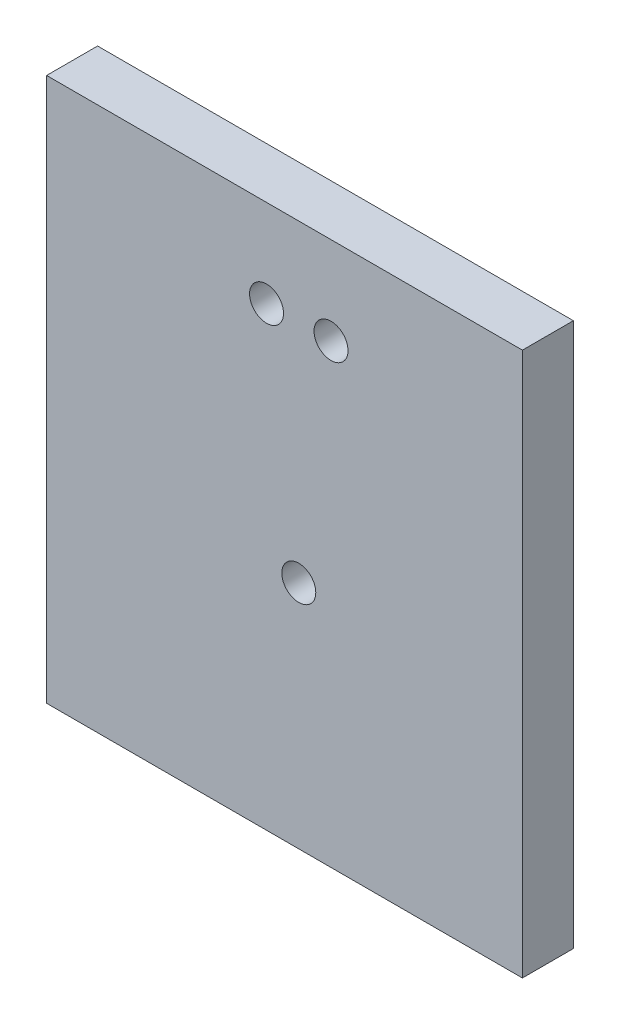
SolidWorks part; units mm, degrees
ref_plane "Front Plane" through (0, 0, 0) normal (0, 0, 1) x (1, 0, 0)
ref_plane "Top Plane" through (0, 0, 0) normal (0, 1, 0) x (1, 0, 0)
ref_plane "Right Plane" through (0, 0, 0) normal (1, 0, 0) x (0, 0, -1)
sketch "Sketch1" plane through (0, 0, 0) normal (0, 0, 1) x (1, 0, 0)
  line L1 (0, 0) -> (-88.9, 0)
  line L2 (0, 0) -> (0, 101.6)
  line L3 (0, 101.6) -> (-88.9, 101.6)
  line L4 (-88.9, 0) -> (-88.9, 101.6)
  dimension "D1" = 88.9
  dimension "D2" = 101.6
extrude "Boss-Extrude1" add sketch "Sketch1" along normal blind 9.525
sketch "Sketch2" plane through (0, 0, 9.525) normal (0, 0, 1) x (1, 0, 0)
  point P0 (-35.7596, 85.2203)
  point P1 (-41.7837, 43.0513)
hole_wizard "1/4 (0.25) Diameter Hole1" positions "Sketch4" profile "Sketch5" hole size "1/4" standard "ANSI Inch" end condition up to next
sketch "Sketch4" plane through (0, 0, 9.525) normal (0, 0, 1) x (1, 0, 0)
  point P0 (-35.7596, 85.2203)
  point P3 (-41.7837, 43.0513)
sketch "Sketch5" plane through (-35.7596, 85.2203, 9.525) normal (1, 0, 0) x (0, -1, 0)
  line L0 (0, 0) -> (0, 9.525)
  line L1 (0, 9.525) -> (3.175, 9.525)
  line L2 (3.175, 9.525) -> (3.175, 0)
  line L5 (3.175, 0) -> (0, 0)
  line L11 (0, -6.35) -> (0, 107.95) construction
  dimension "Thru Hole Dia." = 6.35
  dimension "Thru Hole Depth" = 9.525
sketch "Sketch7" plane through (0, 0, 9.525) normal (0, 0, 1) x (1, 0, 0)
  point P0 (-47.8079, 85.2203)
hole_wizard "1/4 (0.25) Diameter Hole2" positions "Sketch9" profile "Sketch10" hole size "1/4" standard "ANSI Inch" end condition up to next
sketch "Sketch9" plane through (0, 0, 9.525) normal (0, 0, 1) x (1, 0, 0)
  point P0 (-47.8079, 85.2203)
sketch "Sketch10" plane through (-47.8079, 85.2203, 9.525) normal (1, 0, 0) x (0, -1, 0)
  line L0 (0, 0) -> (0, 9.525)
  line L1 (0, 9.525) -> (3.175, 9.525)
  line L2 (3.175, 9.525) -> (3.175, 0)
  line L5 (3.175, 0) -> (0, 0)
  line L11 (0, -6.35) -> (0, 107.95) construction
  dimension "Thru Hole Dia." = 6.35
  dimension "Thru Hole Depth" = 9.525
